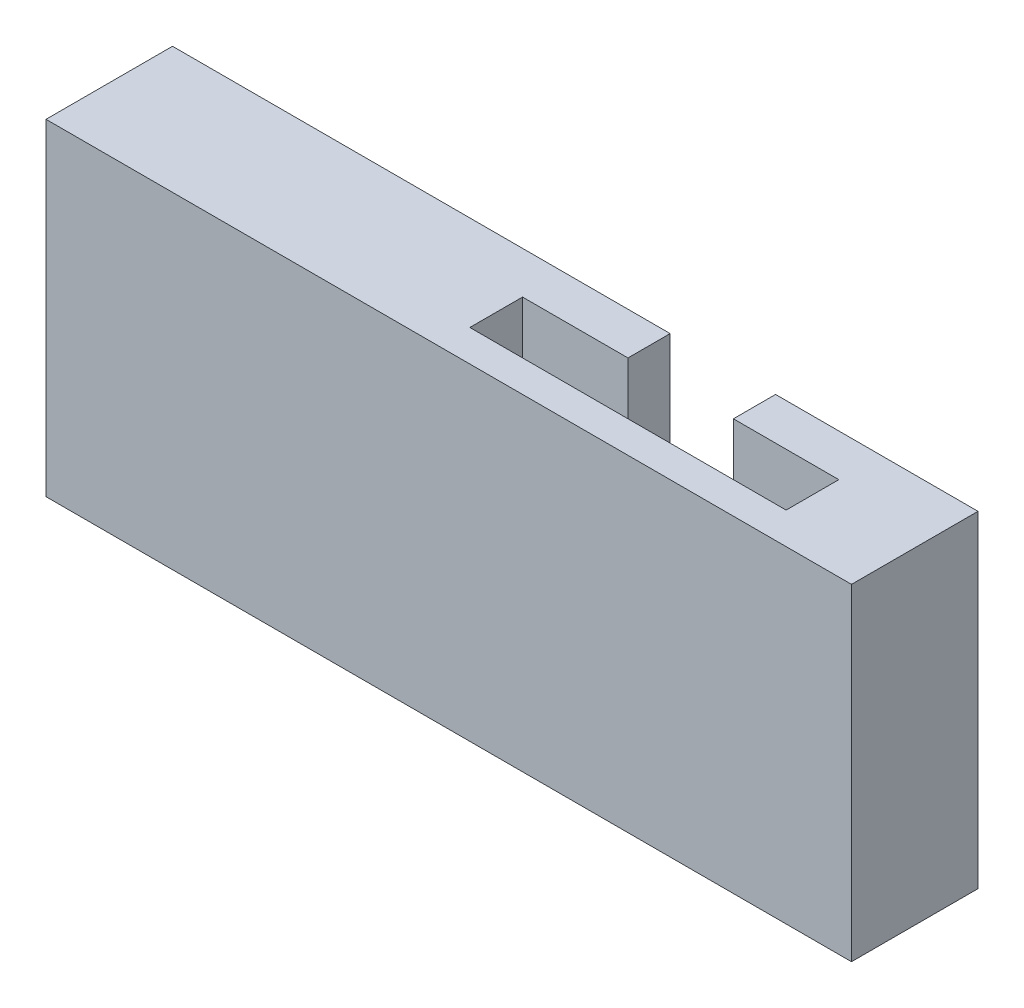
SolidWorks part; units mm, degrees
ref_plane "Front Plane" through (0, 0, 0) normal (0, 0, 1) x (1, 0, 0)
ref_plane "Top Plane" through (0, 0, 0) normal (0, 1, 0) x (1, 0, 0)
ref_plane "Right Plane" through (0, 0, 0) normal (1, 0, 0) x (0, 0, -1)
sketch "Sketch2" plane through (0, 0, 0) normal (0, 0, 1) x (1, 0, 0)
  line L1 (0, 0) -> (39, 0)
  line L2 (0, 0) -> (0, 15.5)
  line L3 (0, 15.5) -> (39, 15.5)
  line L4 (39, 0) -> (39, 15.5)
  dimension "D1" = 15.5
  dimension "D2" = 39
extrude "Boss-Extrude1" add sketch "Sketch2" against normal blind 6
sketch "Sketch3" plane through (0, 15.5, 0) normal (0, 1, 0) x (1, 0, 0)
  line L0 (24, 0) -> (24, 2)
  line L1 (39, 0) -> (0, 0) construction
  line L2 (24, 2) -> (19, 2)
  line L3 (19, 2) -> (19, 4.5)
  line L4 (19, 4.5) -> (34, 4.5)
  line L5 (34, 4.5) -> (34, 2)
  line L6 (34, 2) -> (29, 2)
  line L7 (29, 2) -> (29, 0)
  line L8 (29, 0) -> (24, 0)
  line L10 (39, 6) -> (39, 0) construction
  dimension "D1" = 2
  dimension "D2" = 2.5
  dimension "D3" = 2
  dimension "D4" = 5
  dimension "D5" = 5
  dimension "D6" = 5
  dimension "D7" = 10
extrude "Cut-Extrude1" cut sketch "Sketch3" against normal offset from surface (12.5 mm away) 3 up to face at (19.5, 0, -3)
sketch "Sketch4" plane through (39, 0, 0) normal (1, 0, 0) x (0, 0, -1)
  line L1 (-3.505, 19.2954) -> (16.8149, 19.2954)
  line L2 (-3.505, 19.2954) -> (-3.505, -8.9413)
  line L3 (-3.505, -8.9413) -> (16.8149, -8.9413)
  line L4 (16.8149, 19.2954) -> (16.8149, -8.9413)
extrude "Cut-Extrude2" cut sketch "Sketch4" against normal blind 0.4
sketch "Sketch5" plane through (0, 0, 0) normal (-1, 0, 0) x (0, 0, 1)
  line L1 (-8.1129, 18.4267) -> (2.9706, 18.4267)
  line L2 (-8.1129, 18.4267) -> (-8.1129, -4.1582)
  line L3 (-8.1129, -4.1582) -> (2.9706, -4.1582)
  line L4 (2.9706, 18.4267) -> (2.9706, -4.1582)
extrude "Cut-Extrude3" cut sketch "Sketch5" against normal blind 0.4
mirror "Mirror1" about plane through (0, 0, -6) normal (0, 0, -1) of bodies 104
delete or keep bodies "Body-Delete/Keep 1" type delete bodies bodies 104
